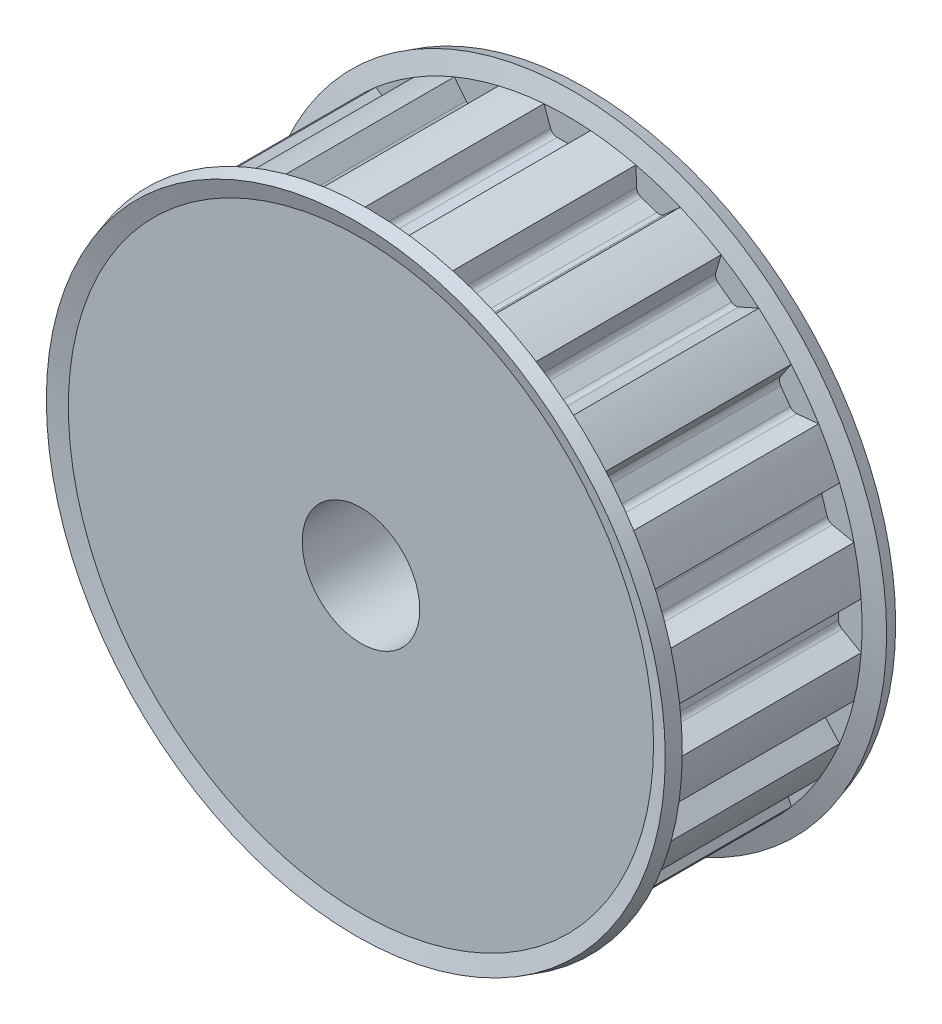
SolidWorks part; units mm, degrees
extrude "BasePulley" add sketch "Sketch1" against normal blind 10.414
sketch "Sketch1" plane through (0, 0, 0) normal (0, 0, 1) x (1, 0, 0)
  circle A0 centre (0, 0) radius 15.9131
  dimension "Outside_dia" = 31.8262
revolve "Flange" add sketch "Sketch2" angle 360 about L11
sketch "Sketch2" plane through (0, 0, 0) normal (1, 0, 0) x (0, 0, -1)
  line L0 (10.414, 15.9131) -> (10.7246, 16.9291)
  line L1 (10.7246, 16.9291) -> (11.429, 16.7137)
  line L2 (5.207, 0) -> (5.207, 66.675) construction
  line L3 (11.429, 16.7137) -> (11.1506, 15.803)
  line L4 (11.1506, 15.803) -> (11.1506, 0)
  line L5 (0, 15.9131) -> (-0.3106, 16.9291)
  line L6 (10.414, -15.9131) -> (10.414, 15.9131) construction
  line L7 (-0.3106, 16.9291) -> (-1.015, 16.7137)
  line L8 (-1.015, 16.7137) -> (-0.7366, 15.803)
  line L9 (-0.7366, 15.803) -> (-0.7366, 0)
  line L10 (10.414, 15.9131) -> (0, 15.9131)
  line L11 (0, 0) -> (38.2092, 0) construction
  line L12 (10.414, 0) -> (0, 0) construction
  line L13 (-0.7366, 0) -> (11.1506, 0)
  dimension "D1" = 5.207
  dimension "Flange_ang" = 17
  dimension "D3" = 0.7366
  dimension "D2" = 15.9131
  dimension "Flange_ht" = 1.016
ref_plane "Plane1" through (0, 0, 0) normal (0, 0, 1) x (1, 0, 0)
ref_plane "Plane2" through (0, 0, 0) normal (0, 1, 0) x (1, 0, 0)
ref_plane "Plane3" through (0, 0, 0) normal (1, 0, 0) x (0, 0, -1)
other "Configuration Table"
sketch "Clipboard" plane through (0, 0, 0) normal (0, 0, 1) x (1, 0, 0)
  line L0 (0, 0) -> (6.604, 0)
  line L1 (0, 0) -> (9.5473, 3.4749)
  line L2 (0, 0) -> (9.5473, -3.4749)
  dimension "Num_grvs" = 20
ref_plane "Plane4" through (0, 0, -5.207) normal (0, 0, 1) x (1, 0, 0)
sketch "Sketch3" plane through (0, 0, -5.207) normal (0, 0, 1) x (1, 0, 0)
  line L0 (-1.2827, 15.9131) -> (-1.2827, 41.3131)
  line L1 (1.2827, 15.9131) -> (1.2827, 41.3131)
  line L2 (0, 0) -> (0, 15.9131) construction
  line L3 (-1.2827, 15.9131) -> (1.2827, 15.9131) construction
  line L4 (-0.5537, 14.6431) -> (0.3295, 14.6431)
  line L5 (1.2827, 15.9131) -> (0.6595, 14.8336)
  line L6 (-1.2827, 15.9131) -> (-0.9117, 14.8938)
  line L7 (1.2827, 41.3131) -> (-1.2827, 41.3131)
  arc A0 (0.3295, 14.6431) -> (0.6595, 14.8336) centre (0.3295, 15.0241) ccw
  arc A2 (-0.9117, 14.8938) -> (-0.5537, 14.6431) centre (-0.5537, 15.0241) ccw
  dimension "Grv_rad_bot" = 0.381
  dimension "Grv_ang" = 50
  dimension "D3" = 20
  dimension "Grv_width" = 2.5654
  dimension "D4" = 25.4
  dimension "D1" = 15.9131
  dimension "Grv_depth" = 1.27
extrude "Groove" cut sketch "Sketch3" against normal mid plane 10.414
pattern_circular "Grooves" count 20 every 18 about axis through (0, 0, -10.414) along (0, 0, 1) of "Groove"
sketch "Sketch4" plane through (0, 0, 0) normal (1, 0, 0) x (0, 0, -1)
  line L0 (0, 0) -> (47.6781, 0) construction
  line L1 (10.414, 0) -> (0, 0) construction
  line L2 (0, 0) -> (-0.254, 0)
  line L3 (-0.254, 0) -> (-0.254, 11.43)
  line L4 (-0.254, 11.43) -> (0, 11.43)
  line L5 (0, 11.43) -> (0, 0)
  line L6 (-0.254, -11.43) -> (0, -11.43) construction
revolve "BaseHub" add sketch "Sketch4" angle 360 about L0
sketch "BorSke" plane through (0, 0, 0.7366) normal (0, 0, 1) x (1, 0, 0)
  circle A0 centre (0, 0) radius 3.175
extrude "Bore" cut sketch "BorSke" against normal through all
sketch "KeySke" plane through (0, 0, 0.7366) normal (0, 0, 1) x (1, 0, 0)
  line L0 (0.127, 3.429) -> (0.127, 0)
  line L1 (0.127, 3.429) -> (-0.127, 3.429)
  line L2 (-0.127, 3.429) -> (-0.127, 0)
  line L3 (-0.127, 0) -> (0.127, 0)
  line L4 (0, 31.75) -> (0, -3.175) construction
  dimension "Width" = 10.414
extrude "Keyway" [suppressed] cut sketch "KeySke" against normal through all
pattern_circular "Keyway2" [suppressed] count 2 every 90
sketch "Sketch6" [suppressed] plane through (0, 0, 1.27) normal (0, 0, 1) x (1, 0, 0)
  circle A0 centre (0, 0) radius 3.175
extrude "Cut-Extrude2" [suppressed] cut sketch "Sketch6" against normal blind 13.716
sketch "Sketch7" plane through (0, 0, -11.1506) normal (0, 0, -1) x (-1, 0, 0)
  circle A0 centre (0, 0) radius 16.7137
  circle A1 centre (0, 0) radius 3.2142
extrude "Boss-Extrude1" add sketch "Sketch7" along normal blind 0.254
equation "\"D1@Plane4\" = \"Width@BasePulley\" / 2"
equation "\"D1@Groove\" = \"Width@BasePulley\""
equation "\"D1@Sketch3\" = \"Outside_dia@Sketch1\" / 2"
equation "\"D1@Sketch2\" = \"Width@BasePulley\" / 2"
equation "\"D2@Sketch2\" = \"Outside_dia@Sketch1\" / 2"
equation "\"D3@Sketch2\" = \"Flange_thickness@Sketch2\""
equation "\"Num_grvs@Clipboard\" = int( \"Num_grvs@Clipboard\" )"
equation "\"Show_grvs@Clipboard\" = int( \"Show_grvs@Clipboard\" )"
equation "\"Show_grvs@Clipboard\" = ((sgn( \"Show_grvs@Clipboard\" - \"Num_grvs@Clipboard\" )-1)*( \"Show_grvs@Clipboard\" - \"Num_grvs@Clipboard\" ))/-2+ \"Num_grvs@Clipboard\""
equation "\"Show_grvs@Clipboard\" = ((sgn( \"Show_grvs@Clipboard\" - 1.0)+1)*( \"Show_grvs@Clipboard\" - 1.0))/2 +1.0"
equation "\"Angle@Grooves\" = 360.0 / \"Num_grvs@Clipboard\""
equation "\"Num_grvs@Grooves\" =  \"Show_grvs@Clipboard\""
equation "\"Offset@KeySke\" = \"T_dim@Clipboard\" - \"Diameter@BorSke\" / 2.0"
equation "\"OAL@Clipboard\" = \"Overall_len@Clipboard\""
equation "\"Hub_depth@Sketch4\" = \"OAL@Clipboard\" - \"Width@BasePulley\""
